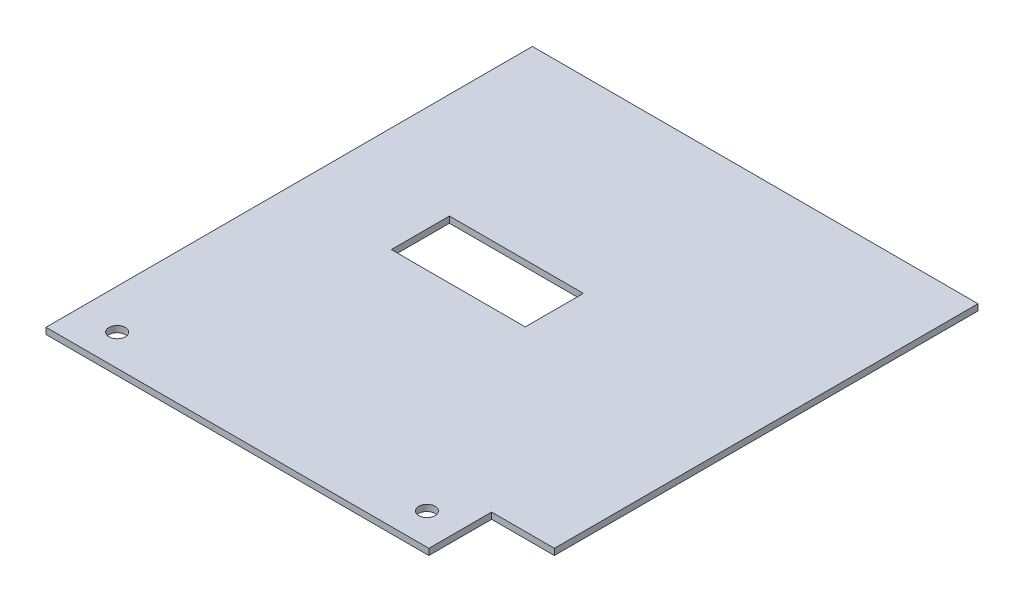
SolidWorks part; units mm, degrees
material "3.0526 (EN-AW 3004)"
ref_plane "Přední rovina" through (0, 0, 0) normal (0, 0, 1) x (1, 0, 0)
ref_plane "Horní rovina" through (0, 0, 0) normal (0, 1, 0) x (1, 0, 0)
ref_plane "Pravá rovina" through (0, 0, 0) normal (1, 0, 0) x (0, 0, -1)
sketch "Skica1" plane through (0, 0, 0) normal (0, 1, 0) x (1, 0, 0)
  line L1 (51.9544, -76.4582) -> (-70.0456, -76.4582)
  line L2 (71.9544, -56.4582) -> (71.9544, 78.5418)
  line L3 (71.9544, 78.5418) -> (-70.0456, 78.5418)
  line L4 (-70.0456, -76.4582) -> (-70.0456, 78.5418)
  line L5 (50.3509, -56.4582) -> (-70.0456, 78.5418) construction
  line L6 (71.9544, 78.5418) -> (-70.0456, -76.4582) construction
  line L9 (71.9544, -56.4582) -> (51.9544, -56.4582)
  line L10 (51.9544, -76.4582) -> (51.9544, -56.4582)
  point P0 (0, 0)
  dimension "D1" = 142
  dimension "D2" = 155
  dimension "D3" = 20
extrude "Přidat vysunutím1" add sketch "Skica1" along normal blind 2
sketch "Skica2" plane through (0, 2, 0) normal (0, 1, 0) x (1, 0, 0)
  line L1 (6.2151, 18.5218) -> (-36.4702, 18.5218)
  line L2 (6.2151, 18.5218) -> (6.2151, 0)
  line L3 (6.2151, 0) -> (-36.4702, 0)
  line L4 (-36.4702, 18.5218) -> (-36.4702, 0)
extrude "Odebrat vysunutím1" cut sketch "Skica2" against normal blind 2
sketch "Skica3" plane through (0, 0, 0) normal (0, -1, 0) x (1, 0, 0)
  line L0 (37.6544, 66.4582) -> (41.3378, 66.4582) construction
  circle A0 centre (41.3378, 66.4582) radius 2.6
  circle A1 centre (-57.3704, 66.4582) radius 2.6
  dimension "D1" = 5.2
extrude "Odebrat vysunutím2" cut sketch "Skica3" against normal blind 2
